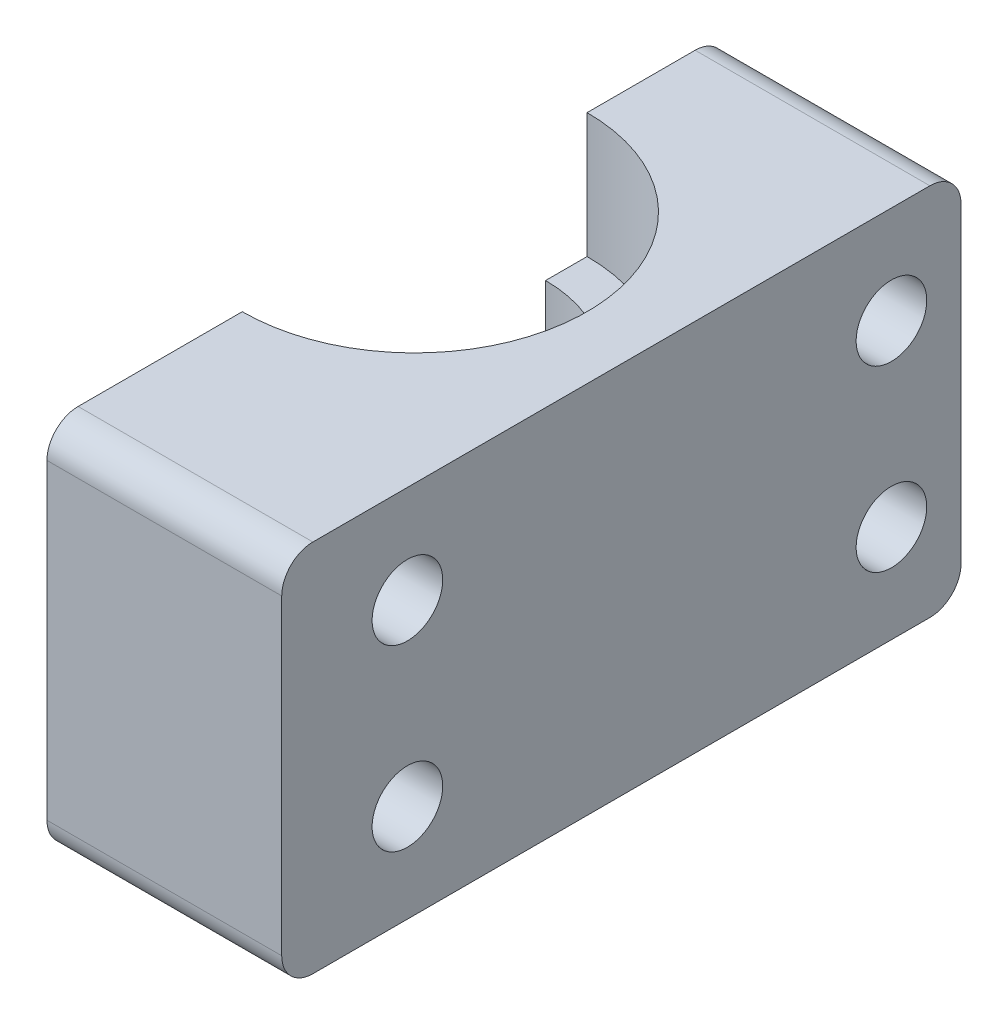
SolidWorks part; units mm, degrees
ref_plane "Front Plane" through (0, 0, 0) normal (0, 0, 1) x (1, 0, 0)
ref_plane "Top Plane" through (0, 0, 0) normal (0, 1, 0) x (1, 0, 0)
ref_plane "Right Plane" through (0, 0, 0) normal (1, 0, 0) x (0, 0, -1)
sketch "Sketch8" plane through (0, 0, 0) normal (1, 0, 0) x (0, 0, -1)
  line L1 (-15, 50) -> (15, 50)
  line L2 (-15, 50) -> (-15, -50)
  line L3 (-15, -50) -> (15, -50)
  line L4 (15, 50) -> (15, -50)
  line L5 (-15, 50) -> (15, -50) construction
  line L6 (-15, -50) -> (15, 50) construction
  point P0 (0, 0)
  dimension "D1" = 30
  dimension "D2" = 100
extrude "Boss-Extrude1" add sketch "Sketch8" along normal blind 100
sketch "Sketch7" plane through (0, 0, 0) normal (1, 0, 0) x (0, 0, -1)
  line L0 (-8.3, 9) -> (-150, 9)
  line L1 (15, 50) -> (-15, 50) construction
  line L2 (-8.3, 9) -> (-8.3, 3)
  line L3 (-8.3, 3) -> (-6.3, 3)
  line L4 (-6.3, 3) -> (-6.3, -3)
  line L5 (-6.3, -3) -> (-8.3, -3)
  line L6 (-8.3, -3) -> (-8.3, -9)
  line L11 (-8.3, -9) -> (-150, -9)
  line L12 (-150, -9) -> (-150, -50)
  line L13 (0, -50) -> (0, 50)
  line L14 (0, 55) -> (0, -55) construction
  line L15 (-150, 9) -> (-150, 50)
  line L16 (-150, 50) -> (0, 50)
  line L17 (-150, -50) -> (0, -50)
  line L18 (-15, -50) -> (15, -50) construction
  line L19 (-15, 9) -> (-15, -9) construction
  line L20 (-15, 50) -> (-15, -50) construction
  line L22 (16.5, 0) -> (-16.5, 0) construction
  point P29 (-15, 0)
  dimension "D1" = 8.3
  dimension "D2" = 6
  dimension "D3" = 6.3
  dimension "D4" = 6
  dimension "D5" = 18
  dimension "D9" = 150
revolve "Cut-Revolve3" cut sketch "Sketch7" angle 360 about L13
sketch "Sketch9" plane through (0, 9, 0) normal (0, 1, 0) x (1, 0, 0)
  line L0 (-55, 0) -> (55, 0) construction
  line L1 (11.3, -15) -> (100, -15)
  line L2 (11.3, -15) -> (11.3, 15)
  line L3 (11.3, 15) -> (100, 15)
  line L4 (100, -15) -> (100, 15)
  line L5 (11.3, -15) -> (100, 15) construction
  line L6 (11.3, 15) -> (100, -15) construction
  line L7 (100, 15) -> (100, -15) construction
  line L8 (0, -15) -> (100, -15) construction
  line L9 (8.3, 15) -> (8.3, -15) construction
  line L10 (100, 15) -> (0, 15) construction
  arc A1 (0, -8.3) -> (0, 8.3) centre (0, 0) ccw construction
  point P0 (55.65, 0)
  dimension "D1" = 3
extrude "Cut-Extrude1" cut sketch "Sketch9" against normal through all
sketch "Sketch10" plane through (0, 0, 0) normal (-1, 0, 0) x (0, 0, 1)
  line L0 (-11.65, 4.3) -> (-11.65, 9) construction
  line L1 (-11.65, -4.3) -> (11.65, -4.3) construction
  line L2 (-11.65, -4.3) -> (-11.65, 4.3) construction
  line L3 (-11.65, 4.3) -> (11.65, 4.3) construction
  line L4 (11.65, -4.3) -> (11.65, 4.3) construction
  line L5 (-11.65, -4.3) -> (11.65, 4.3) construction
  line L6 (-11.65, 4.3) -> (11.65, -4.3) construction
  line L7 (-15, 9) -> (-8.3, 9) construction
  circle A0 centre (-11.65, 4.3) radius 1.7
  circle A1 centre (-11.65, -4.3) radius 1.7
  circle A2 centre (11.65, -4.3) radius 1.7
  circle A3 centre (11.65, 4.3) radius 1.7
  point P0 (0, 0)
  dimension "D1" = 3.4
  dimension "D2" = 4.7
extrude "Cut-Extrude2" cut sketch "Sketch10" against normal through all
other "Move Face1" face at (5.65, 0, 15) parameters "D1"=2.7
fillet "Fillet1" radius 1.5 4 edges at (5.65, 9, -15) (5.65, -9, -15) (5.65, -9, 17.7) (5.65, 9, 17.7)
equation "\"linear_bearing_l\"= 35"
equation "\"linear_bearing_d\"= 12"
equation "\"t\"= 3"
equation "\"axes_offset\"= 44.5"
equation "\"fan_b\"= 30"
equation "\"E3D_r\"= 12.8"
equation "\"fan_screws_b\"= 24"
equation "\"fan_screws_l\"= 15"
equation "\"M3_tap_d\"= 2.6"
equation "\"M3_d\"= 3.4"
equation "\"E3D_screws_l\"= 15"
equation "\"M3_nut_s\"= 5.9"
equation "\"M3_nut_m\"= 1.8"
equation "\"cable_ties_d\"= 3"
equation "\"D1@Sketch8\"=\"fan_b\""
equation "\"D2@Sketch8\"=100"
equation "\"D1@Sketch9\"=\"t\""
equation "\"D1@Sketch10\"=\"M3_d\""
equation "\"D2@Sketch10\"=\"M3_d\" / 2 + \"t\""
equation "\"D1@Fillet1\"=\"t\" / 2"
